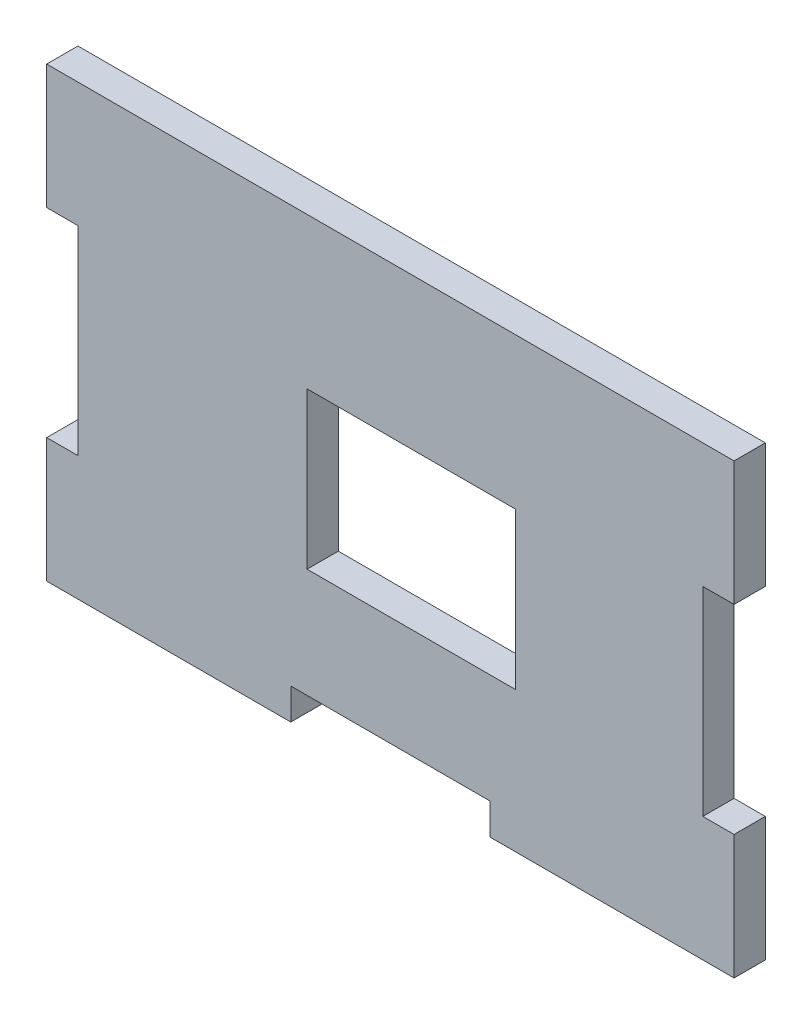
SolidWorks part; units mm, degrees
ref_plane "Front Plane" through (0, 0, 0) normal (0, 0, 1) x (1, 0, 0)
ref_plane "Top Plane" through (0, 0, 0) normal (0, 1, 0) x (1, 0, 0)
ref_plane "Right Plane" through (0, 0, 0) normal (1, 0, 0) x (0, 0, -1)
sketch "Sketch1" plane through (0, 0, 0) normal (0, 0, 1) x (1, 0, 0)
  line L0 (41.7123, -43.6262) -> (41.7123, -55.5637)
  line L1 (41.7123, -55.5637) -> (44.7123, -55.5637)
  line L2 (44.7123, -55.5637) -> (44.7123, -74.6887)
  line L3 (44.7123, -74.6887) -> (41.7123, -74.6887)
  line L4 (41.7123, -74.6887) -> (41.7123, -86.6262)
  line L5 (41.7123, -86.6262) -> (65.1498, -86.6262)
  line L6 (65.1498, -86.6262) -> (65.1498, -83.6262)
  line L7 (65.1498, -83.6262) -> (84.2748, -83.6262)
  line L8 (84.2748, -83.6262) -> (84.2748, -86.6262)
  line L9 (84.2748, -86.6262) -> (103.3998, -86.6262)
  line L10 (103.3998, -86.6262) -> (107.7123, -86.6262)
  line L11 (107.7123, -86.6262) -> (107.7123, -74.6887)
  line L12 (107.7123, -74.6887) -> (104.7123, -74.6887)
  line L13 (104.7123, -74.6887) -> (104.7123, -55.5637)
  line L14 (104.7123, -55.5637) -> (107.7123, -55.5637)
  line L15 (107.7123, -55.5637) -> (107.7123, -43.6262)
  line L16 (107.7123, -43.6262) -> (41.7123, -43.6262)
extrude "Boss-Extrude1" add sketch "Sketch1" along normal blind 3 contours L16 L0 L1 L2 L3 L4 L5 L6 L7 L8 L9 L10 L11 L12 L13 L14 L15
sketch "Sketch2" plane through (0, 0, 3) normal (0, 0, 1) x (1, 0, 0)
  line L0 (94.9831, -58.1327) -> (59.4231, -58.1327) construction
  line L1 (66.7123, -58.1327) -> (86.7123, -58.1327)
  line L2 (66.7123, -58.1327) -> (66.7123, -73.1327)
  line L3 (66.7123, -73.1327) -> (86.7123, -73.1327)
  line L4 (86.7123, -58.1327) -> (86.7123, -73.1327)
  line L5 (44.7123, -55.5637) -> (44.7123, -74.6887) construction
  dimension "D1" = 15
  dimension "D2" = 20
  dimension "D3" = 22
extrude "Cut-Extrude2" cut sketch "Sketch2" against normal blind 10
